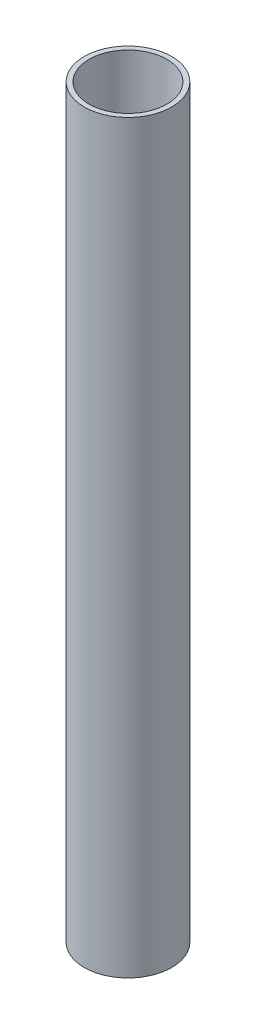
SolidWorks part; units mm, degrees
ref_plane "Front Plane" through (0, 0, 0) normal (0, 0, 1) x (1, 0, 0)
ref_plane "Top Plane" through (0, 0, 0) normal (0, 1, 0) x (1, 0, 0)
ref_plane "Right Plane" through (0, 0, 0) normal (1, 0, 0) x (0, 0, -1)
sketch "Sketch1" plane through (0, 0, 0) normal (0, 1, 0) x (1, 0, 0)
  circle A0 centre (0, 0) radius 50.8
  circle A1 centre (0, 0) radius 57.15
  dimension "D1" = 101.6
  dimension "D2" = 114.3
extrude "Boss-Extrude1" add sketch "Sketch1" along normal mid plane 973.328
